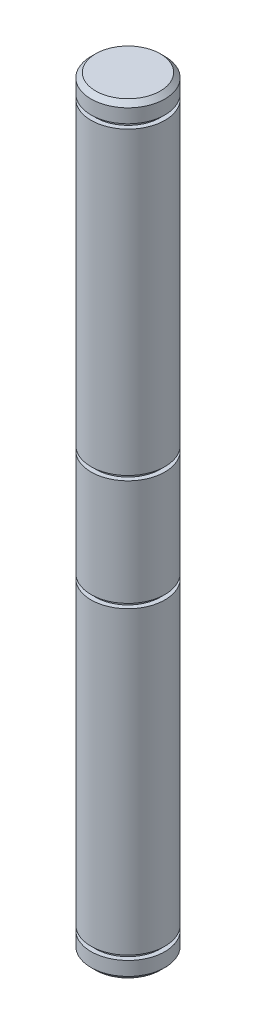
SolidWorks part; units mm, degrees
ref_plane "前视基准面" through (0, 0, 0) normal (0, 0, 1) x (1, 0, 0)
ref_plane "上视基准面" through (0, 0, 0) normal (0, 1, 0) x (1, 0, 0)
ref_plane "右视基准面" through (0, 0, 0) normal (1, 0, 0) x (0, 0, -1)
sketch "Sketch2" plane through (0, 0, 0) normal (0, 0, 1) x (1, 0, 0)
  line L0 (0, 0) -> (8, 0)
  line L1 (0, 0) -> (0, -8.7917) construction
  line L2 (8, 0) -> (8, 11.5)
  line L3 (8, 11.5) -> (7, 11.5)
  line L4 (7, 11.5) -> (7, 12.5)
  line L5 (7, 12.5) -> (8, 12.5)
  line L6 (8, 12.5) -> (8, 77.5)
  line L7 (8, 77.5) -> (7, 77.5)
  line L8 (7, 77.5) -> (7, 78.5)
  line L9 (7, 78.5) -> (8, 78.5)
  line L10 (8, 78.5) -> (8, 82.5)
  line L11 (8, 82.5) -> (0, 82.5)
  line L12 (0, 82.5) -> (0, 0)
  line L14 (0, 0) -> (-14.3562, 0) construction
  dimension "D1" = 1
  dimension "D2" = 1
  dimension "D3" = 5
  dimension "D4" = 70
  dimension "D5" = 16
  dimension "D6" = 165
revolve "Revolve1" add sketch "Sketch2" angle 360 about L12
mirror "Mirror1" about plane through (0, 0, 0) normal (0, 1, 0) of "Revolve1"
chamfer "Chamfer1" distance 1 angle 45 2 edges at (-8, 82.5, 0) (-8, -82.5, 0)
